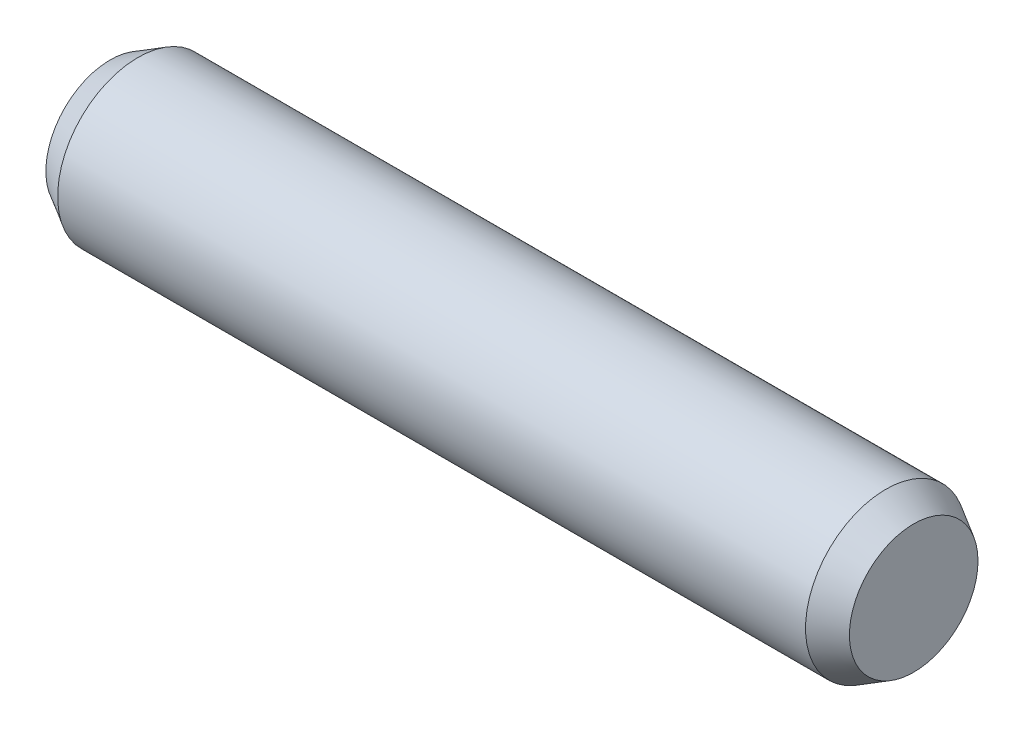
SolidWorks part; units mm, degrees
ref_plane "Front Plane" through (0, 0, 0) normal (0, 0, 1) x (1, 0, 0)
ref_plane "Top Plane" through (0, 0, 0) normal (0, 1, 0) x (1, 0, 0)
ref_plane "Right Plane" through (0, 0, 0) normal (1, 0, 0) x (0, 0, -1)
sketch "Sketch4" plane through (0, 0, 0) normal (1, 0, 0) x (0, 0, -1)
  circle A0 centre (0, 0) radius 5
extrude "Boss-Extrude2" add sketch "Sketch4" along normal blind 50
chamfer "Chamfer1" distance 1 angle 60 1 edges at (0, 0, -5)
ref_plane "Plane1" through (25, 0, 0) normal (-1, 0, 0) x (0, 0, 1)
chamfer "Chamfer2" distance 1 angle 60 1 edges at (50, 0, -5)
